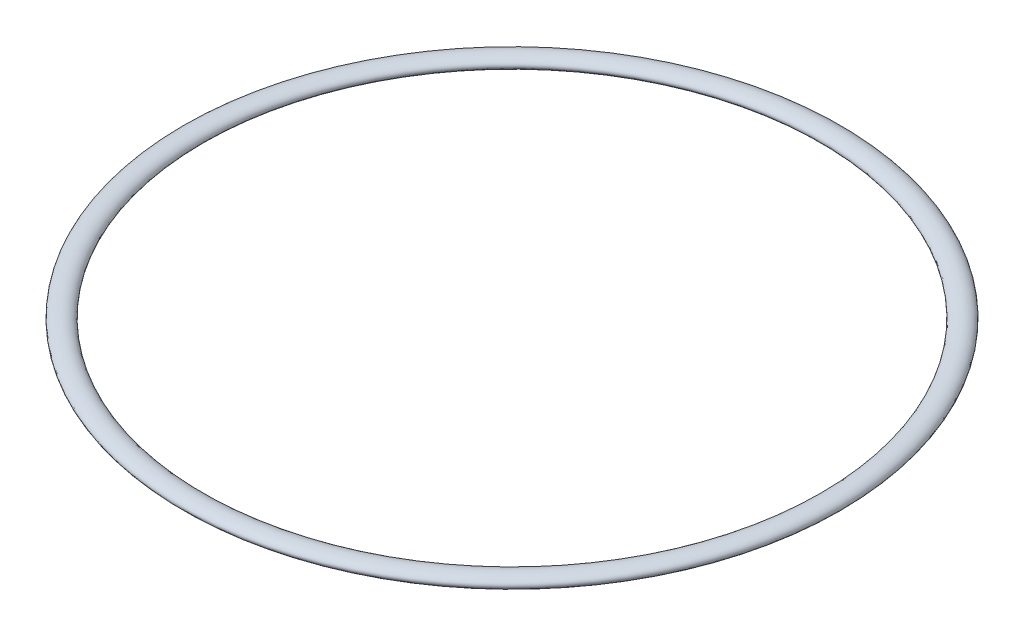
SolidWorks part; units mm, degrees
ref_plane "Front Plane" through (0, 0, 0) normal (0, 0, 1) x (1, 0, 0)
ref_plane "Top Plane" through (0, 0, 0) normal (0, 1, 0) x (1, 0, 0)
ref_plane "Right Plane" through (0, 0, 0) normal (1, 0, 0) x (0, 0, -1)
sketch "Reconstructed nominal axial profile" plane through (0, 0, 0) normal (0, 0, 1) x (1, 0, 0)
  line L0 (0, -500) -> (0, 50) construction
  ellipse E0 centre (39.425, 0) end of major axis (40.7894, 0) minor radius 0.725
revolve "Native revolved geometry" add sketch "Reconstructed nominal axial profile" angle 360 about L0
